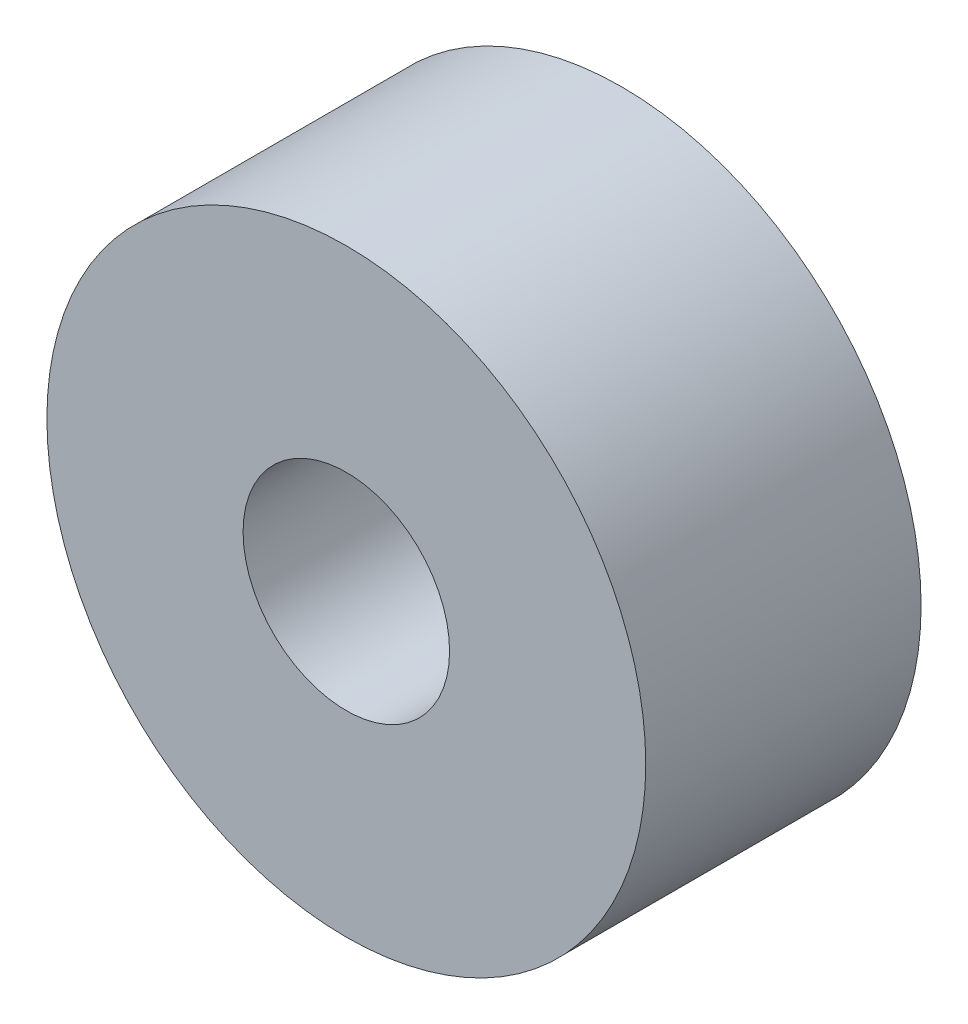
SolidWorks part; units mm, degrees
ref_plane "前视基准面" through (0, 0, 0) normal (0, 0, 1) x (1, 0, 0)
ref_plane "上视基准面" through (0, 0, 0) normal (0, 1, 0) x (1, 0, 0)
ref_plane "右视基准面" through (0, 0, 0) normal (1, 0, 0) x (0, 0, -1)
sketch "草图1" plane through (0, 0, 0) normal (0, 0, 1) x (1, 0, 0)
  circle A0 centre (0, 0) radius 1.5
  circle A1 centre (0, 0) radius 4.35
extrude "凸台-拉伸1" add sketch "草图1" along normal blind 4
